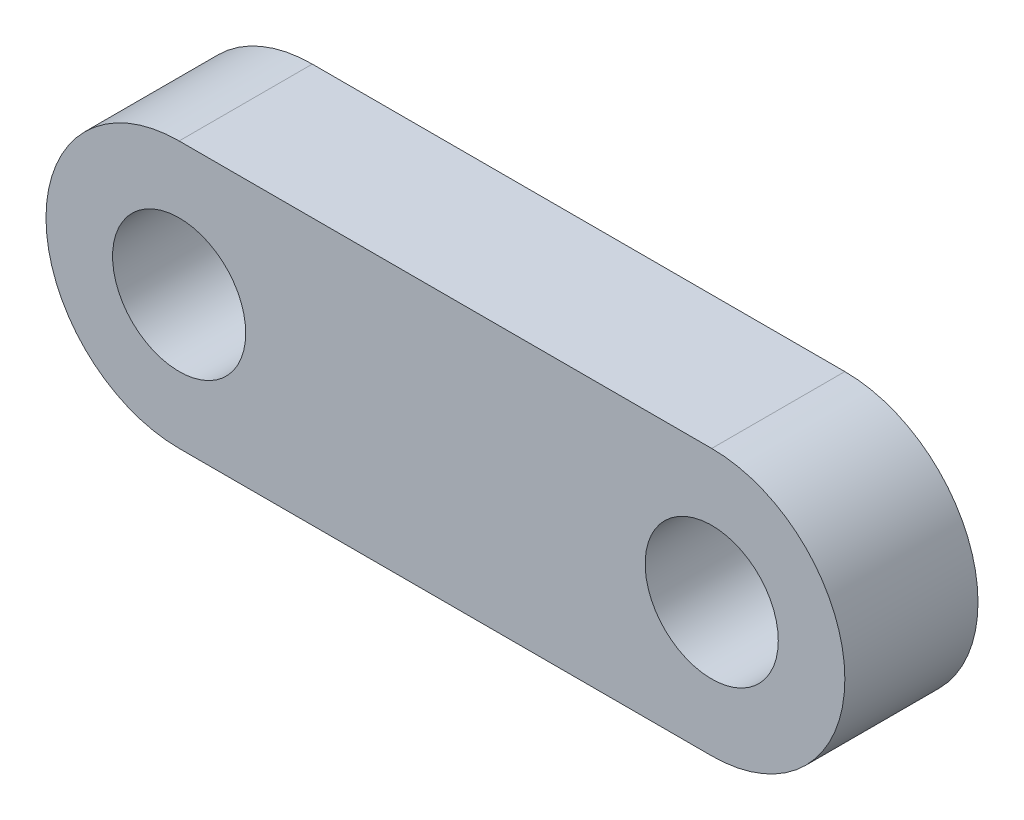
SolidWorks part; units mm, degrees
ref_plane "Front Plane" through (0, 0, 0) normal (0, 0, 1) x (1, 0, 0)
ref_plane "Top Plane" through (0, 0, 0) normal (0, 1, 0) x (1, 0, 0)
ref_plane "Right Plane" through (0, 0, 0) normal (1, 0, 0) x (0, 0, -1)
sketch "Sketch1" plane through (0, 0, 0) normal (0, 0, 1) x (1, 0, 0)
  line L0 (-40, 25) -> (-60, 25) construction
  line L1 (-40, 20) -> (-60, 20)
  line L2 (-40, 30) -> (-60, 30)
  circle A0 centre (-40, 25) radius 2.5
  arc A2 (-40, 20) -> (-40, 30) centre (-40, 25) ccw
  arc A3 (-60, 30) -> (-60, 20) centre (-60, 25) ccw
  circle A4 centre (-60, 25) radius 2.5
  point P3 (-50, 25)
  dimension "D1" = 20
  dimension "D2" = 5
  dimension "D3" = 5
  dimension "D4" = 10
extrude "Boss-Extrude1" add sketch "Sketch1" against normal blind 5
